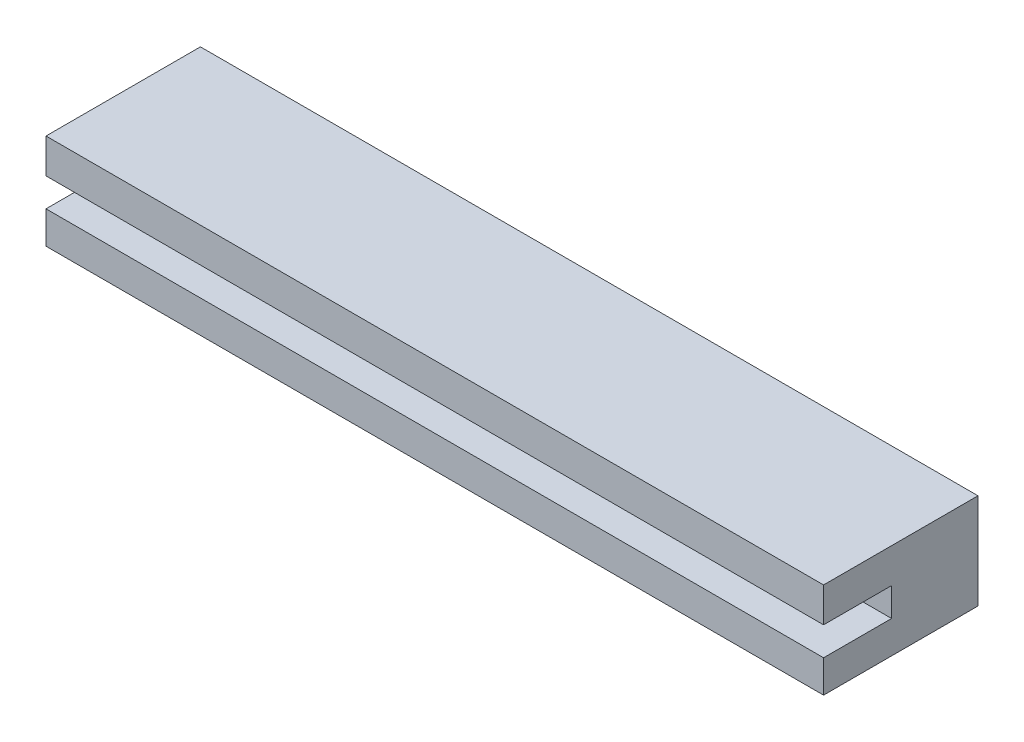
SolidWorks part; units mm, degrees
ref_plane "Front Plane" through (0, 0, 0) normal (0, 0, 1) x (1, 0, 0)
ref_plane "Top Plane" through (0, 0, 0) normal (0, 1, 0) x (1, 0, 0)
ref_plane "Right Plane" through (0, 0, 0) normal (1, 0, 0) x (0, 0, -1)
sketch "Sketch1" plane through (0, 0, 0) normal (1, 0, 0) x (0, 0, -1)
  line L0 (4, 0) -> (4, -5.6134)
  line L1 (0, 0) -> (4, 0)
  line L2 (0, 0) -> (0, -2.032)
  line L3 (0, -2.032) -> (4, -2.032)
  line L4 (4, 0) -> (4, -2.032)
  line L5 (0, -3.7084) -> (4, -3.7084)
  line L6 (0, -3.7084) -> (0, -5.6134)
  line L7 (0, -5.6134) -> (4, -5.6134)
  line L8 (4, -3.7084) -> (4, -5.6134)
  line L9 (9.08, -5.6134) -> (9.08, 0)
  line L10 (9.08, 0) -> (4, 0)
  line L11 (4, -5.6134) -> (9.08, -5.6134)
  dimension "D1" = 2.032
  dimension "D2" = 1.905
  dimension "D3" = 1.6764
  dimension "D4" = 4
  dimension "D5" = 5.08
extrude "Boss-Extrude1" add sketch "Sketch1" along normal blind 45.72 contours L2 L3 L0 L1 | L0 L11 L9 L10 | L6 L7 L0 L5
